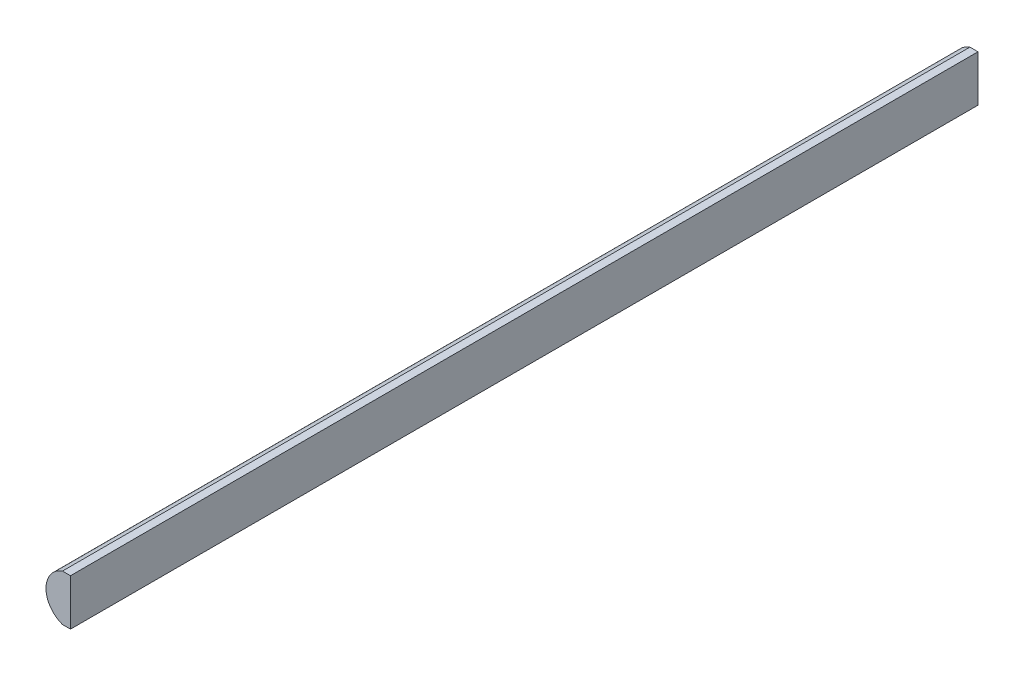
SolidWorks part; units mm, degrees
ref_plane "Front Plane" through (0, 0, 0) normal (0, 0, 1) x (1, 0, 0)
ref_plane "Top Plane" through (0, 0, 0) normal (0, 1, 0) x (1, 0, 0)
ref_plane "Right Plane" through (0, 0, 0) normal (1, 0, 0) x (0, 0, -1)
sketch "Sketch1" plane through (0, 0, 0) normal (0, 0, 1) x (1, 0, 0)
  line L1 (0, 2.55) -> (-0.8874, 2.55)
  line L3 (0, -2.55) -> (-0.8874, -2.55)
  line L4 (-2.7, 0) -> (-2.7, 9.9087) construction
  line L5 (0, 2.55) -> (0, -2.55)
  arc A0 (-0.8874, -2.55) -> (-0.8874, 2.55) centre (0, 0) cw
  dimension "D1" = 2.7
  dimension "D2" = 5.1
extrude "Boss-Extrude1" add sketch "Sketch1" along normal blind 100
